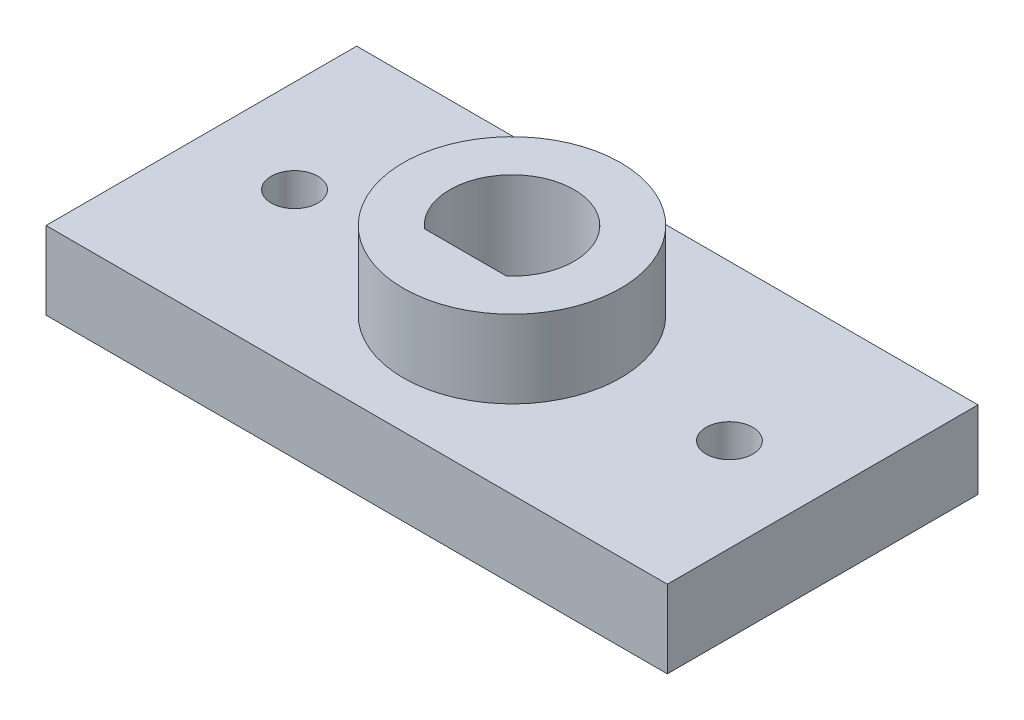
SolidWorks part; units mm, degrees
ref_plane "Front Plane" through (0, 0, 0) normal (0, 0, 1) x (1, 0, 0)
ref_plane "Top Plane" through (0, 0, 0) normal (0, 1, 0) x (1, 0, 0)
ref_plane "Right Plane" through (0, 0, 0) normal (1, 0, 0) x (0, 0, -1)
sketch "Sketch1" plane through (0, 0, 0) normal (0, 1, 0) x (1, 0, 0)
  line L0 (-20, 0) -> (20, 0) construction
  line L1 (-20, 10) -> (20, 10)
  line L2 (-20, 10) -> (-20, -10)
  line L3 (-20, -10) -> (20, -10)
  line L4 (20, 10) -> (20, -10)
  line L5 (-20, 10) -> (20, -10) construction
  line L6 (-20, -10) -> (20, 10) construction
  line L7 (0, -4) -> (0, -3) construction
  line L8 (-2.6458, -3) -> (2.6458, -3)
  circle A0 centre (14, 0) radius 1.5
  circle A1 centre (-14, 0) radius 1.5
  circle A2 centre (0, 0) radius 4 construction
  arc A3 (-2.6458, -3) -> (2.6458, -3) centre (0, 0) cw
  point P0 (0, 0)
  point P9 (0, 0)
  point P20 (0, -3)
  dimension "D1" = 3
  dimension "D2" = 3
  dimension "D3" = 6
  dimension "D4" = 6
  dimension "D8" = 8
  dimension "D5" = 40
  dimension "D6" = 20
  dimension "D7" = 1
extrude "Boss-Extrude1" add sketch "Sketch1" along normal blind 5
sketch "Sketch2" plane through (0, 5, 0) normal (0, 1, 0) x (1, 0, 0)
  line L0 (0, -4) -> (0, -3) construction
  line L1 (-2.6458, -3) -> (2.6458, -3) construction
  line L2 (-2.6458, -3) -> (2.6458, -3) construction
  circle A0 centre (0, 0) radius 4 construction
  circle A1 centre (0, 0) radius 7
  arc A2 (-2.6458, -3) -> (2.6458, -3) centre (0, 0) cw
  point P12 (0, -3)
  line M11 (2.6458, -3) -> (-2.6458, -3)
  arc M12 (-2.6458, -3) -> (2.6458, -3) centre (0, 0) cw
  dimension "D1" = 8
  dimension "D2" = 14
extrude "Boss-Extrude2" add sketch "Sketch2" along normal blind 5 contours A1 M12 M11
